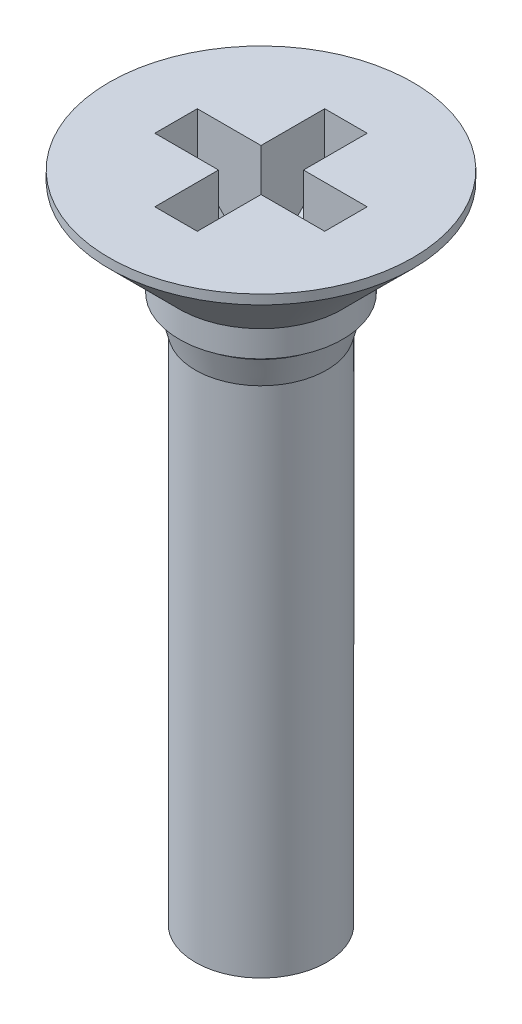
SolidWorks part; units mm, degrees
ref_plane "Vorderseite" through (0, 0, 0) normal (0, 0, 1) x (1, 0, 0)
ref_plane "Oben" through (0, 0, 0) normal (0, 1, 0) x (1, 0, 0)
ref_plane "Rechts" through (0, 0, 0) normal (1, 0, 0) x (0, 0, -1)
sketch "Skizze1" plane through (0, 0, 0) normal (0, 0, 1) x (1, 0, 0)
  line L0 (0, 0) -> (4.65, 0)
  line L1 (4.65, 0) -> (4.65, -0.29)
  line L2 (4.65, -0.29) -> (2.5, -2.44)
  line L3 (2.24, -3.24) -> (2.24, -3.4398)
  line L4 (2.24, -3.4398) -> (2.0095, -4.3)
  line L5 (2.0095, -4.3) -> (2.0095, -16)
  line L6 (2.0095, -16) -> (0, -16)
  line L7 (0, 0) -> (0, -16) construction
  line L8 (0, 0) -> (0, -16)
  line L10 (2.5, -2.44) -> (2.5, -3.24)
  line L12 (2.5, -3.24) -> (2.24, -3.24)
  point P3 (2.24, -2.7)
  dimension "D1" = 45
  dimension "D2" = 15
  dimension "K" = 2.7
  dimension "DA" = 9.3
  dimension "DK" = 4.019
  dimension "L" = 16
  dimension "DG" = 5
  dimension "A" = 1.6
  dimension "DF" = 4.48
  dimension "P" = 0.8
revolve "Basis-Rotation" add sketch "Skizze1" angle 360 about L7
sketch "Skizze2" plane through (0, 0, 0) normal (0, 0, 1) x (1, 0, 0)
  line L0 (0, -3.2) -> (0, 0) construction
  line L1 (0, 0) -> (0, -16) construction
  line L2 (-1, -3.2) -> (1, -3.2)
  line L3 (2.6, 0) -> (2.6, -1.6)
  line L4 (2.6, -1.6) -> (1, -3.2)
  line L5 (2.6, 0) -> (-2.6, 0)
  line L6 (-2.6, -1.6) -> (-1, -3.2)
  line L7 (-2.6, 0) -> (-2.6, -1.6)
  line L8 (0, -1.6) -> (2.6, -1.6) construction
  line L9 (4.65, 0) -> (-4.65, 0) construction
  line L11 (2.5, -2.44) -> (4.65, -0.29) construction
  point P11 (0, 0)
  dimension "M" = 5.2
  dimension "T" = 3.2
extrude "Kreuzschlitz1 H" cut sketch "Skizze2" against normal blind 0.65 and the other way blind 0.65
sketch "Skizze3" plane through (0, 0, 0) normal (1, 0, 0) x (0, 0, -1)
  line L0 (0, -3.2) -> (0, 0) construction
  line L2 (-1, -3.2) -> (1, -3.2)
  line L3 (2.6, 0) -> (2.6, -1.6)
  line L4 (2.6, -1.6) -> (1, -3.2)
  line L5 (2.6, 0) -> (-2.6, 0)
  line L6 (-2.6, -1.6) -> (-1, -3.2)
  line L7 (-2.6, 0) -> (-2.6, -1.6)
  line L8 (0, -1.6) -> (2.6, -1.6) construction
  point P11 (0, 0)
extrude "Kreuzschlitz2 H" cut sketch "Skizze3" against normal blind 0.65 and the other way blind 0.65
sketch "Skizze4" plane through (2.4522, 0, -1.8507) normal (0, 1, 0) x (-1, 0, 0)
  line L0 (7.3522, 1.8507) -> (-2.4478, 1.8507) construction
  line L1 (2.4522, -3.0493) -> (2.4522, 6.7507) construction
  line L2 (-2.4478, 1.0342) -> (-2.4478, 2.6672)
  line L3 (-2.4478, 1.0342) -> (0.0059, 1.0342)
  line L4 (0.0059, 1.0342) -> (0.8191, 0.6258)
  line L5 (1.2273, 0.2176) -> (-1.0126, -1.6141)
  line L6 (0.8191, 0.6258) -> (-1.0126, -1.6141)
  line L7 (1.6357, -0.5956) -> (1.2273, 0.2176)
  line L8 (1.6357, -3.0493) -> (1.6357, -0.5956)
  line L9 (1.6357, -3.0493) -> (3.2687, -3.0493)
  line L10 (3.2687, -3.0493) -> (3.2687, -0.5956)
  line L11 (3.2687, -0.5956) -> (3.6772, 0.2176)
  line L12 (2.4522, 1.8507) -> (-1.0126, -1.6141) construction
  line L13 (4.0854, 0.6258) -> (5.917, -1.6141)
  line L14 (3.6772, 0.2176) -> (5.917, -1.6141)
  line L15 (4.8986, 1.0342) -> (4.0854, 0.6258)
  line L16 (7.3522, 1.0342) -> (4.8986, 1.0342)
  line L17 (7.3522, 1.0342) -> (7.3522, 2.6672)
  line L18 (7.3522, 2.6672) -> (4.8986, 2.6672)
  line L19 (4.8986, 2.6672) -> (4.0854, 3.0757)
  line L20 (3.6772, 3.4839) -> (5.917, 5.3156)
  line L21 (4.0854, 3.0757) -> (5.917, 5.3156)
  line L22 (3.2687, 4.2971) -> (3.6772, 3.4839)
  line L23 (3.2687, 6.7507) -> (3.2687, 4.2971)
  line L24 (1.6357, 6.7507) -> (3.2687, 6.7507)
  line L25 (1.6357, 6.7507) -> (1.6357, 4.2971)
  line L26 (1.6357, 4.2971) -> (1.2273, 3.4839)
  line L27 (0.8191, 3.0757) -> (-1.0126, 5.3156)
  line L28 (1.2273, 3.4839) -> (-1.0126, 5.3156)
  line L29 (0.0059, 2.6672) -> (0.8191, 3.0757)
  line L30 (-2.4478, 2.6672) -> (0.0059, 2.6672)
  circle A0 centre (2.4522, 1.8507) radius 4.9 construction
  circle A1 centre (2.4522, 1.8507) radius 2.0415 construction
  circle A2 centre (2.4522, 1.8507) radius 2.579 construction
  dimension "X2" = 4.083
  dimension "X1" = 5.158
  dimension "M" = 9.8
  dimension "D3" = 5.725
  dimension "X3" = 1.633
sketch "Sketch1" plane through (0, -16, 0) normal (0, -1, 0) x (1, 0, 0)
  circle A0 centre (0, 0) radius 2.0095
  dimension "D1" = 4.019
extrude "Boss-Extrude1" add sketch "Sketch1" along normal blind 4
